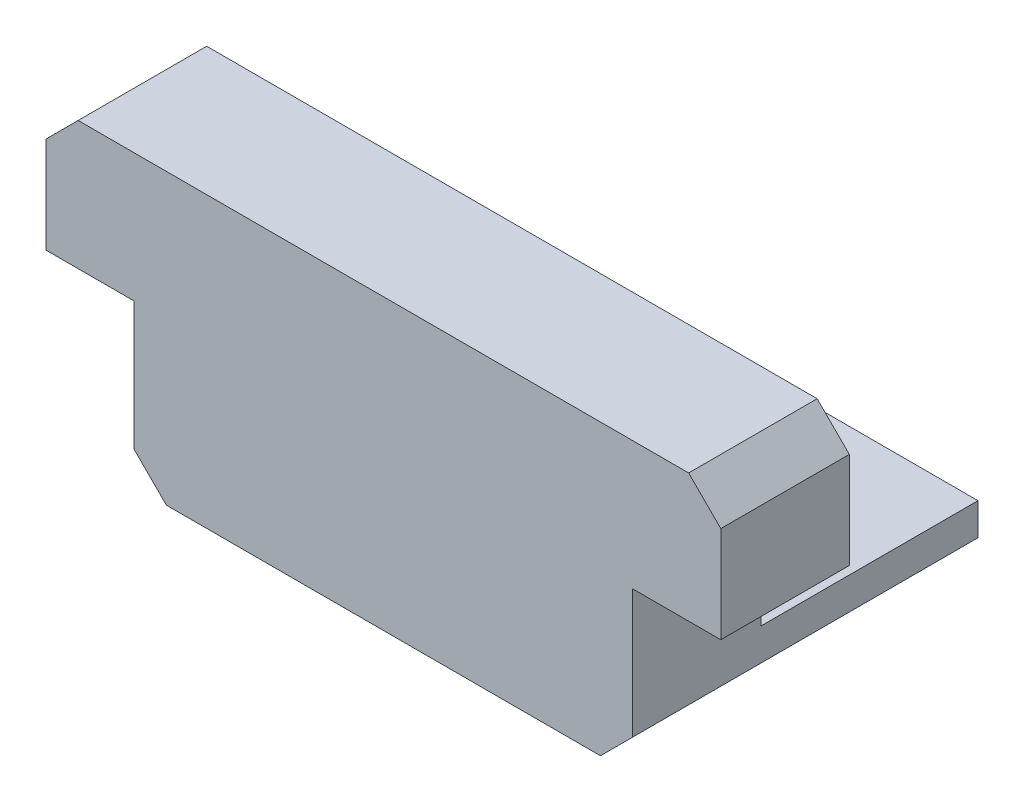
SolidWorks part; units mm, degrees
ref_plane "Спереди" through (0, 0, 0) normal (0, 0, 1) x (1, 0, 0)
ref_plane "Сверху" through (0, 0, 0) normal (0, 1, 0) x (1, 0, 0)
ref_plane "Справа" through (0, 0, 0) normal (1, 0, 0) x (0, 0, -1)
sketch "Эскиз1" plane through (0, 0, 0) normal (0, 0, 1) x (1, 0, 0)
  line L0 (-0.0095, 2) -> (1.9905, 0)
  line L1 (1.9905, 0) -> (29.0095, 0)
  line L2 (-0.0095, 2) -> (-0.0095, 10)
  line L3 (-3.5, 17.9905) -> (34.5, 17.9905)
  line L4 (-3.5, 17.9905) -> (-5.5, 15.9905)
  line L5 (15.5, 19) -> (15.5, 22.0666) construction
  line L6 (31.0095, 2) -> (29.0095, 0)
  line L7 (-16.9933, 10) -> (-0.0095, 10) construction
  line L8 (31.0095, 2) -> (31.0095, 10)
  line L9 (31.0095, 10) -> (36.5, 10)
  line L10 (-0.0095, 10) -> (-5.5, 10)
  line L11 (-5.5, 15.9905) -> (-5.5, 10)
  line L12 (34.5, 17.9905) -> (36.5, 15.9905)
  line L13 (36.5, 15.9905) -> (36.5, 10)
  point P14 (-5.5, 17.9905)
  point P20 (15.5, 17.9905)
  dimension "D7" = 2
extrude "Вытянуть1" add sketch "Эскиз1" along normal blind 21.5
sketch "Эскиз2" plane through (0, 0, 0) normal (0, 0, -1) x (-1, 0, 0)
  line L1 (-37.1561, 20.6115) -> (6.2175, 20.6115)
  line L2 (-37.1561, 20.6115) -> (-37.1561, 4)
  line L3 (-37.1561, 4) -> (6.2175, 4)
  line L4 (6.2175, 20.6115) -> (6.2175, 4)
  line L5 (0.0095, 4) -> (16.9933, 4) construction
extrude "Вырез-Вытянуть1" cut sketch "Эскиз2" against normal blind 13.5
